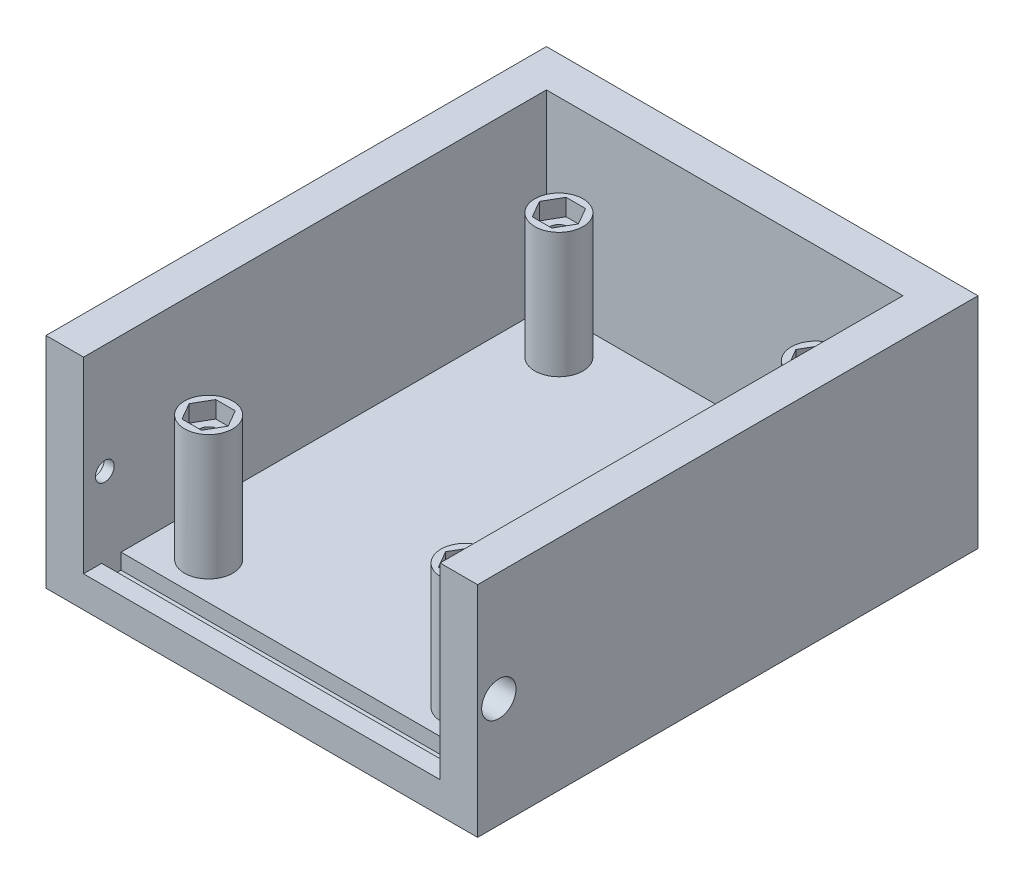
SolidWorks part; units mm, degrees
ref_plane "Front Plane" through (0, 0, 0) normal (0, 0, 1) x (1, 0, 0)
ref_plane "Top Plane" through (0, 0, 0) normal (0, 1, 0) x (1, 0, 0)
ref_plane "Right Plane" through (0, 0, 0) normal (1, 0, 0) x (0, 0, -1)
sketch "Sketch1" plane through (0, 0, 0) normal (0, 1, 0) x (1, 0, 0)
  line L0 (-32.5, 40) -> (32.5, -40) construction
  line L1 (-32.5, -40) -> (32.5, -40)
  line L2 (-32.5, -40) -> (-32.5, 40)
  line L3 (-32.5, 40) -> (32.5, 40)
  line L4 (32.5, -40) -> (32.5, 40)
  line L5 (32.5, 40) -> (-32.5, -40) construction
  point P4 (0, 0)
  dimension "D1" = 65
  dimension "D2" = 80
extrude "Boss-Extrude1" add sketch "Sketch1" along normal blind 5
sketch "Sketch2" plane through (0, 5, 0) normal (0, 1, 0) x (1, 0, 0)
  line L0 (-28.5, 34) -> (28.5, -34) construction
  line L1 (-28.5, -34) -> (28.5, -34)
  line L2 (-28.5, -34) -> (-28.5, 34)
  line L3 (-28.5, 34) -> (28.5, 34)
  line L4 (28.5, -34) -> (28.5, 34)
  line L5 (28.5, 34) -> (-28.5, -34) construction
  line L7 (-32.5, -40) -> (32.5, -40)
  line L8 (-32.5, -40) -> (-32.5, 40)
  line L9 (-32.5, 40) -> (32.5, 40)
  line L10 (32.5, -40) -> (32.5, 40)
  point P4 (0, 0)
  dimension "D1" = 68
  dimension "D2" = 57
extrude "Boss-Extrude2" add sketch "Sketch2" along normal blind 30
sketch "Sketch3" plane through (0, 5, 0) normal (0, 1, 0) x (1, 0, 0)
  line L6 (-20.5, 28) -> (20.5, 28) construction
  line L7 (-20.5, 28) -> (-20.5, -28) construction
  line L8 (-20.5, -28) -> (20.5, -28) construction
  line L9 (20.5, 28) -> (20.5, -28) construction
  line L10 (-20.5, 28) -> (20.5, -28) construction
  line L11 (-20.5, -28) -> (20.5, 28) construction
  circle A0 centre (-20.5, -28) radius 3.85
  circle A1 centre (20.5, -28) radius 3.85
  circle A2 centre (20.5, 28) radius 3.85
  circle A3 centre (-20.5, 28) radius 3.85
  point P1 (0, 0)
  point P4 (0, 0)
  dimension "D5" = 7.7
  dimension "D8" = 7.7
  dimension "D13" = 7.7
  dimension "D16" = 7.7
  dimension "D2" = 56
  dimension "D3" = 41
extrude "Boss-Extrude3" add sketch "Sketch3" along normal blind 20
hole_wizard "Ø3.0mm Dowel Hole1" positions "Sketch10" profile "Sketch5" hole size "Ø3.0" standard "ISO"
sketch "Sketch10" plane through (0, 25, 0) normal (0, 1, 0) x (1, 0, 0)
  point P0 (-20.5, 28)
  point P3 (20.5, 28)
  point P6 (20.5, -28)
  point P9 (-20.5, -28)
sketch "Sketch5" plane through (-20.5, 25, -28) normal (1, 0, 0) x (0, 0, 1)
  line L0 (0, 0) -> (0, 9.4013)
  line L1 (0, 9.4013) -> (1.5, 8.5)
  line L2 (1.5, 8.5) -> (1.5, 0.025)
  line L3 (1.5, 0.025) -> (1.525, 0)
  line L5 (1.525, 0) -> (0, 0)
  line L6 (-1.5, 0.025) -> (-1.525, 0) construction
  line L10 (0, 9.4013) -> (-1.5, 8.5) construction
  line L11 (0, -6.35) -> (0, 107.95) construction
  dimension "Hole Dia." = 3
  dimension "Hole Depth" = 8.5
  dimension "Near C'Sink Dia." = 3.05
  dimension "Near C'Sink Angle" = 90
  dimension "Drill Angle" = 118
sketch "Sketch8" plane through (0, 25, 0) normal (0, 1, 0) x (1, 0, 0)
  line L1 (-17.3823, 28) -> (-18.9412, 30.7)
  line L2 (-18.9412, 30.7) -> (-22.0588, 30.7)
  line L3 (-22.0588, 30.7) -> (-23.6177, 28)
  line L4 (-23.6177, 28) -> (-22.0588, 25.3)
  line L5 (-22.0588, 25.3) -> (-18.9412, 25.3)
  line L6 (-18.9412, 25.3) -> (-17.3823, 28)
  circle A0 centre (-20.5, 28) radius 2.7 construction
  circle A1 centre (-20.5, 28) radius 1.525 construction
  dimension "D1" = 2.7
  dimension "D2" = 3.1177
extrude "Cut-Extrude1" cut sketch "Sketch8" against normal blind 2.7
mirror "Mirror1" about plane through (0, 0, 0) normal (0, 0, 1) of "Cut-Extrude1" second plane through (0, 0, 0) second plane normal (1, 0, 0)
sketch "Sketch13" plane through (32.5, 0, 0) normal (1, 0, 0) x (0, 0, -1)
  line L0 (-40, 17.5) -> (40, 17.5) construction
  line L1 (-40, 35) -> (-40, 0) construction
  line L2 (40, 35) -> (40, 0) construction
  circle A1 centre (-36.6, 17.5) radius 2.75
  dimension "D1" = 5.5
  dimension "D3" = 3.4
extrude "Cut-Extrude4" cut sketch "Sketch13" against normal blind 2.4
sketch "Sketch14" plane through (32.5, 0, 0) normal (1, 0, 0) x (0, 0, -1)
  circle A0 centre (-36.6, 17.5) radius 1.5
extrude "Cut-Extrude5" cut sketch "Sketch14" against normal blind 4
mirror "Mirror2" about plane through (0, 0, 0) normal (1, 0, 0) of "Cut-Extrude5", "Cut-Extrude4"
sketch "Sketch11" plane through (0, 35, 0) normal (0, 1, 0) x (1, 0, 0)
  line L0 (-32.5, -40) -> (32.5, -40) construction
  line L1 (-28.5, -34) -> (28.5, -34)
  line L2 (-28.5, -34) -> (-28.5, -40)
  line L3 (-28.5, -40) -> (28.5, -40)
  line L4 (28.5, -34) -> (28.5, -40)
  line L5 (-28.5, -34) -> (28.5, -40) construction
  line L6 (-28.5, -40) -> (28.5, -34) construction
  line L7 (28.5, -34) -> (28.5, 34) construction
  point P4 (0, -37)
  dimension "D1" = 6
extrude "Cut-Extrude2" cut sketch "Sketch11" against normal blind 30
sketch "Sketch15" plane through (0, 5, 0) normal (0, 1, 0) x (1, 0, 0)
  line L0 (-28.5, 34) -> (-28.5, -40) construction
  line L1 (-28.5, -34) -> (28.5, -34)
  line L2 (-28.5, -34) -> (-28.5, -37.1)
  line L3 (-28.5, -37.1) -> (28.5, -37.1)
  line L4 (28.5, -34) -> (28.5, -37.1)
  line L5 (-28.5, -34) -> (28.5, -37.1) construction
  line L6 (-28.5, -37.1) -> (28.5, -34) construction
  line L7 (28.5, -40) -> (28.5, 34) construction
  line L8 (-28.5, -40) -> (28.5, -40) construction
  point P4 (0, -35.55)
  dimension "D1" = 2.9
  dimension "D2" = 3.1
extrude "Cut-Extrude6" cut sketch "Sketch15" against normal blind 2.5
sketch "Sketch16" plane through (-32.5, 0, 0) normal (-1, 0, 0) x (0, 0, 1)
  line L1 (-40, 35) -> (40, 35)
  line L2 (-40, 35) -> (-40, 0)
  line L3 (-40, 0) -> (40, 0)
  line L4 (40, 35) -> (40, 0)
  line L5 (-40, 35) -> (40, 0) construction
  line L6 (-40, 0) -> (40, 35) construction
  circle A0 centre (36.6, 17.5) radius 2.75
  point P4 (0, 17.5)
  dimension "D1" = 5.5
extrude "Boss-Extrude4" add sketch "Sketch16" along normal blind 2
mirror "Mirror3" about plane through (0, 0, 0) normal (1, 0, 0) of "Boss-Extrude4"
